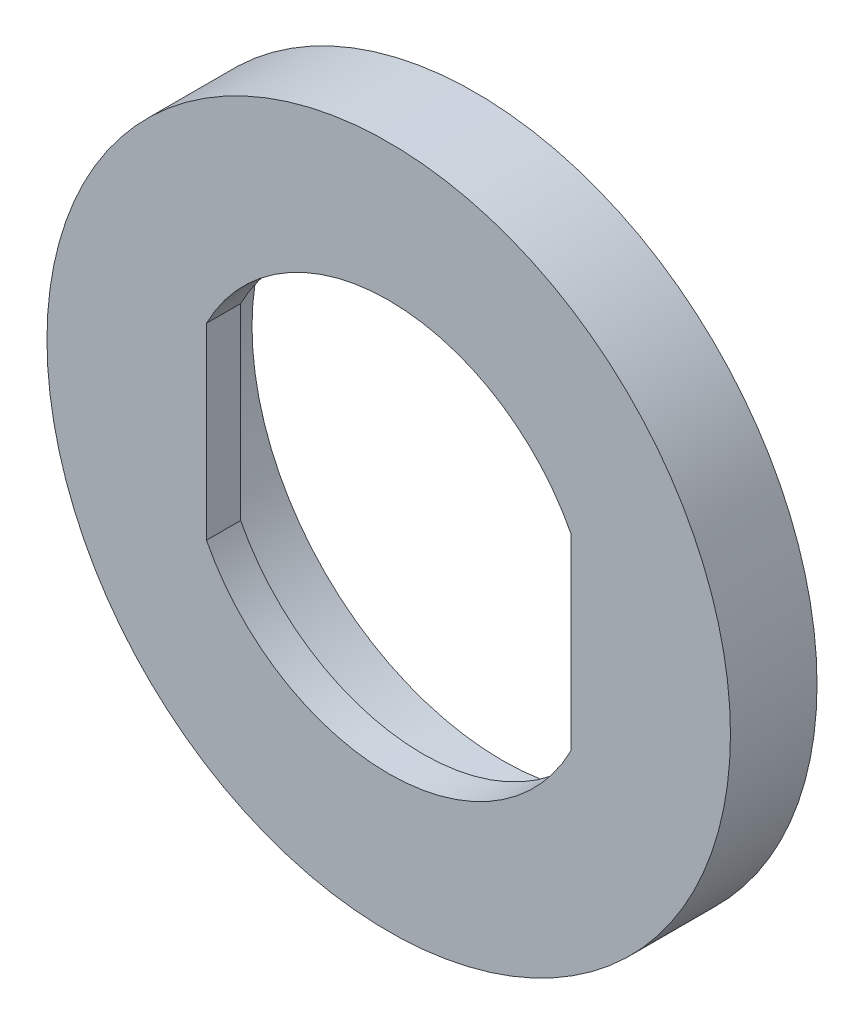
SolidWorks part; units mm, degrees
ref_plane "前视基准面" through (0, 0, 0) normal (0, 0, 1) x (1, 0, 0)
ref_plane "上视基准面" through (0, 0, 0) normal (0, 1, 0) x (1, 0, 0)
ref_plane "右视基准面" through (0, 0, 0) normal (1, 0, 0) x (0, 0, -1)
sketch "草图1" plane through (0, 0, 0) normal (0, 0, 1) x (1, 0, 0)
  circle A0 centre (0, 0) radius 13
  circle A1 centre (0, 0) radius 11
  dimension "D1" = 26
  dimension "D2" = 22
extrude "拉伸1" add sketch "草图1" along normal blind 4
sketch "草图2" plane through (0, 0, 4) normal (0, 0, 1) x (1, 0, 0)
  circle A0 centre (0, 0) radius 15
  dimension "D1" = 30
extrude "拉伸2" add sketch "草图2" against normal blind 2.8 and the other way blind 1
sketch "草图3" plane through (0, 0, 1.2) normal (0, 0, -1) x (-1, 0, 0)
  circle A0 centre (0, 0) radius 11 construction
  circle A1 centre (0, 0) radius 11
extrude "切除-拉伸1" cut sketch "草图3" against normal blind 2.3
sketch "草图4" plane through (0, 0, 3.5) normal (0, 0, -1) x (-1, 0, 0)
  line L0 (0, -10.7512) -> (0, 17.6028) construction
  line L1 (-8, -4.1231) -> (-8, 4.1231)
  line L2 (8, -4.1231) -> (8, 4.1231)
  arc A0 (-8, -4.1231) -> (8, -4.1231) centre (0, 0) ccw
  arc A3 (8, 4.1231) -> (-8, 4.1231) centre (0, 0) ccw
  dimension "D1" = 18
  dimension "D2" = 16
extrude "切除-拉伸2" cut sketch "草图4" against normal blind 2
